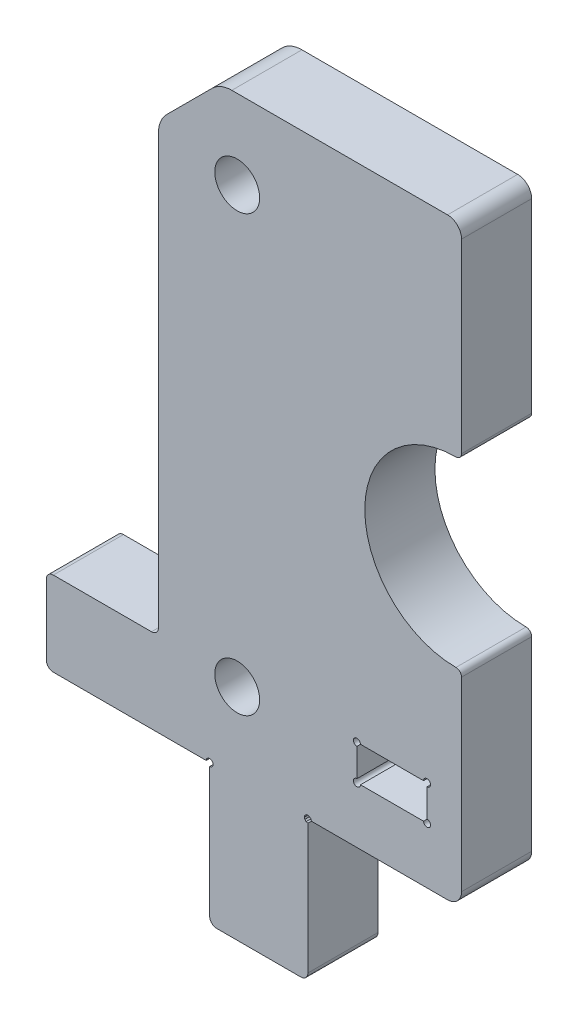
SolidWorks part; units mm, degrees
ref_plane "Plan de face" through (0, 0, 0) normal (0, 0, 1) x (1, 0, 0)
ref_plane "Plan de dessus" through (0, 0, 0) normal (0, 1, 0) x (1, 0, 0)
ref_plane "Plan de droite" through (0, 0, 0) normal (1, 0, 0) x (0, 0, -1)
ref_plane "Plan1" through (0, 0, 0) normal (0, 0, -1) x (-1, 0, 0)
sketch "Esquisse1" plane through (0, 0, 0) normal (0, 0, -1) x (-1, 0, 0)
  line L0 (-29.61, 24.25) -> (-29.61, 10)
  line L1 (-13.2284, 52.3) -> (-29.61, 52.3)
  line L2 (-22.15, 14) -> (-22.15, 17.0502) construction
  line L3 (-29.61, 52.3) -> (-29.61, 38.05)
  line L4 (-21.6787, 16.5) -> (-28.5641, 16.5) construction
  line L5 (-27.15, 16.9858) -> (-27.15, 13.6557) construction
  line L6 (-27.6792, 14) -> (-21.4382, 14) construction
  line L59 (-29.61, 10) -> (-18.9, 10)
  line L60 (-18.9, 10) -> (-18.8665, 10.125)
  line L61 (-18.8665, 10.125) -> (-18.775, 10.2165)
  line L62 (-18.775, 10.2165) -> (-18.65, 10.25)
  line L63 (-18.65, 10.25) -> (-18.525, 10.2165)
  line L64 (-18.525, 10.2165) -> (-18.4335, 10.125)
  line L65 (-18.4335, 10.125) -> (-18.4, 10)
  line L66 (-18.4, 10) -> (-18.4335, 9.875)
  line L67 (-18.4335, 9.875) -> (-18.525, 9.7835)
  line L68 (-18.525, 9.7835) -> (-18.65, 9.75)
  line L69 (-18.65, 9.75) -> (-18.65, 0.5)
  line L73 (-18.15, 0) -> (-12.15, 0)
  line L77 (-11.65, 0.5) -> (-11.65, 9.75)
  line L78 (-11.65, 9.75) -> (-11.775, 9.7835)
  line L79 (-11.775, 9.7835) -> (-11.8665, 9.875)
  line L80 (-11.8665, 9.875) -> (-11.9, 10)
  line L81 (-11.9, 10) -> (-11.8665, 10.125)
  line L82 (-11.8665, 10.125) -> (-11.775, 10.2165)
  line L83 (-11.775, 10.2165) -> (-11.65, 10.25)
  line L84 (-11.65, 10.25) -> (-11.525, 10.2165)
  line L85 (-11.525, 10.2165) -> (-11.4335, 10.125)
  line L86 (-11.4335, 10.125) -> (-11.4, 10)
  line L87 (-11.4, 10) -> (-0.4999, 10)
  line L91 (0.0001, 10.5) -> (0.0001, 15.5)
  line L95 (-0.4999, 16) -> (-7.4999, 16)
  line L99 (-7.9999, 16.5) -> (-7.9999, 47.0716)
  line L102 (-8.5857, 48.4858) -> (-11.8142, 51.7142)
  line L124 (-22.4, 14) -> (-26.9, 14)
  line L134 (-27.15, 14.25) -> (-27.15, 16.25)
  line L144 (-26.9, 16.5) -> (-22.4, 16.5)
  line L154 (-22.15, 16.25) -> (-22.15, 14.25)
  arc A0 (-29.21, 24.65) -> (-29.21, 37.65) centre (-29.21, 31.15) ccw
  circle A1 centre (-13.61, 46.65) radius 1.6
  circle A2 centre (-13.61, 15.65) radius 1.6
  arc A3 (0.0001, 15.5) -> (-0.4999, 16) centre (-0.4999, 15.5) ccw
  arc A4 (-7.4999, 16) -> (-7.9999, 16.5) centre (-7.4999, 16.5) cw
  arc A5 (0.0001, 10.5) -> (-0.4999, 10) centre (-0.4999, 10.5) cw
  arc A6 (-11.65, 0.5) -> (-12.15, 0) centre (-12.15, 0.5) cw
  arc A7 (-18.15, 0) -> (-18.65, 0.5) centre (-18.15, 0.5) cw
  arc A8 (-29.21, 37.65) -> (-29.61, 38.05) centre (-29.21, 38.05) cw
  arc A9 (-29.21, 24.65) -> (-29.61, 24.25) centre (-29.21, 24.25) ccw
  arc A10 (-22.4, 14) -> (-22.15, 14.25) centre (-22.15, 14) ccw
  arc A11 (-22.15, 16.25) -> (-22.4, 16.5) centre (-22.15, 16.5) ccw
  arc A12 (-26.9, 16.5) -> (-27.15, 16.25) centre (-27.15, 16.5) ccw
  arc A13 (-27.15, 14.25) -> (-26.9, 14) centre (-27.15, 14) ccw
  arc A14 (-7.9999, 47.0716) -> (-8.5857, 48.4858) centre (-10, 47.0716) ccw
  arc A15 (-11.8142, 51.7142) -> (-13.2284, 52.3) centre (-13.2284, 50.3) ccw
  dimension "D1" = 13
  dimension "D2" = 3.2
  dimension "D3" = 3.2
  dimension "D5" = 15.5
  dimension "D6" = 15.6
  dimension "D7" = 15.6
  dimension "D10" = 16
  dimension "D11" = 5.65
  dimension "D17" = 0.5
  dimension "D18" = 0.5
  dimension "D19" = 0.5
  dimension "D20" = 0.5
  dimension "D4" = 31
  dimension "D8" = 31.15
  dimension "D9" = 29.21
  dimension "D12" = 29.2101
  dimension "D13" = 6
  dimension "D14" = 7
  dimension "D15" = 10.56
  dimension "D16" = 21.15
extrude "Boss.-Extru.1" add sketch "Esquisse1" against normal blind 5
fillet "Congé1" radius 1 2 edges at (29.61, 52.3, 2.5) (29.61, 10, 2.5)
